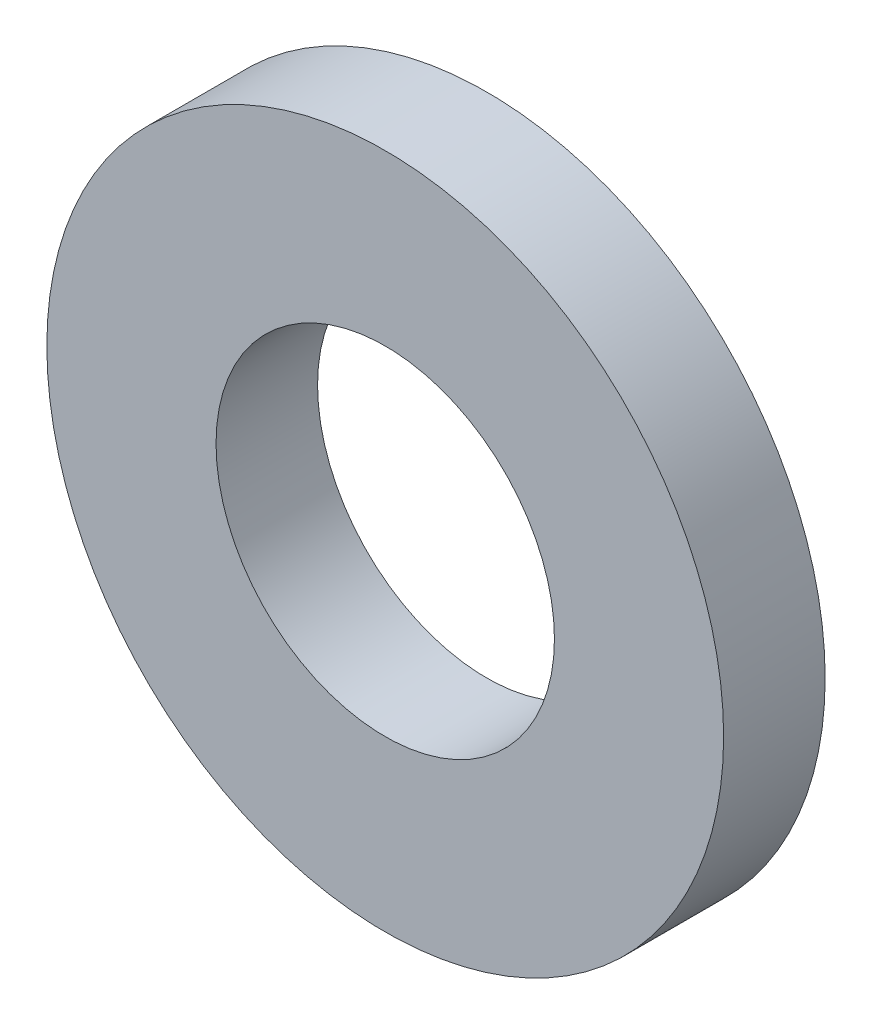
SolidWorks part; units mm, degrees
ref_plane "Plan de face" through (0, 0, 0) normal (0, 0, 1) x (1, 0, 0)
ref_plane "Plan de dessus" through (0, 0, 0) normal (0, 1, 0) x (1, 0, 0)
ref_plane "Plan de droite" through (0, 0, 0) normal (1, 0, 0) x (0, 0, -1)
sketch "Esquisse1" plane through (0, 0, 0) normal (0, 0, 1) x (1, 0, 0)
  circle A0 centre (0, 0) radius 2
  circle A1 centre (0, 0) radius 4
extrude "Boss.-Extru.1" add sketch "Esquisse1" along normal blind 1.2
